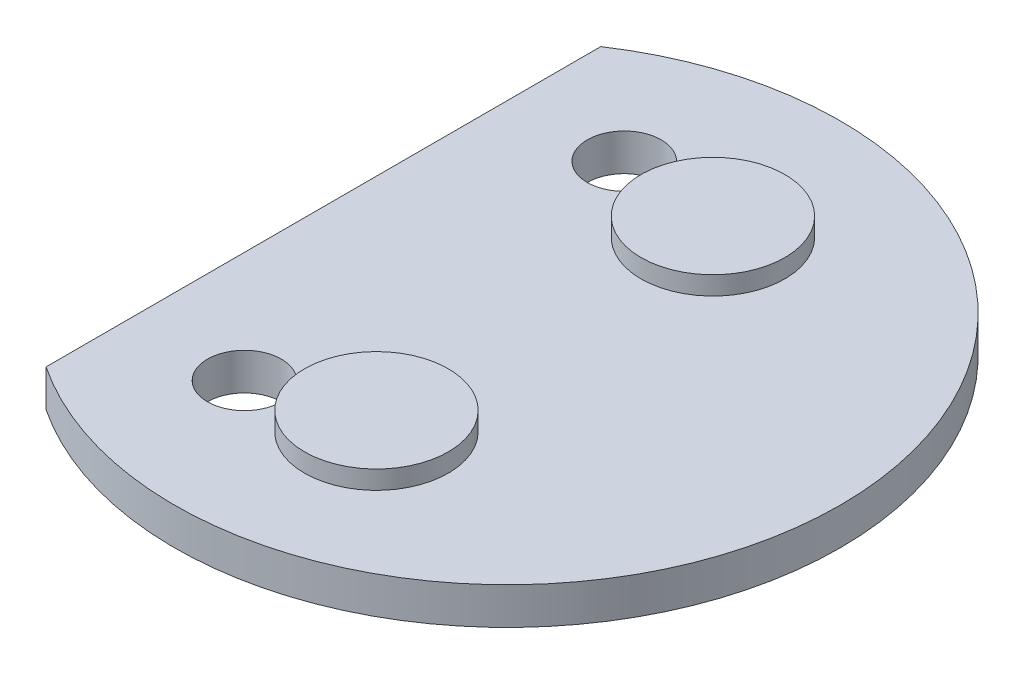
SolidWorks part; units mm, degrees
ref_plane "Plano frontal" through (0, 0, 0) normal (0, 0, 1) x (1, 0, 0)
ref_plane "Plano superior" through (0, 0, 0) normal (0, 1, 0) x (1, 0, 0)
ref_plane "Plano direito" through (0, 0, 0) normal (1, 0, 0) x (0, 0, -1)
sketch "Esboço4" plane through (0, 0, 0) normal (0, 1, 0) x (1, 0, 0)
  line L0 (4.9701, 2.0623) -> (4.9701, -12.9377)
  circle A1 centre (9.9451, -5.4377) radius 9
  dimension "D4" = 18
  dimension "D3" = 15
other "Alinhar grupo1"
extrude "Ressalto-extrusão2" add sketch "Esboço4" along normal blind 1.5 contours L0 A1
sketch "Esboço5" plane through (0, 1.5, 0) normal (0, 1, 0) x (1, 0, 0)
  circle A1 centre (10.9534, -0.8885) radius 1.945
  circle A2 centre (10.9534, -9.9869) radius 1.945
  circle A3 centre (8.28, -5.1612) radius 15.7275
extrude "Corte-extrusão1" cut sketch "Esboço5" against normal blind 0.5
sketch "Esboço7" plane through (0, 1, 0) normal (0, 1, 0) x (1, 0, 0)
  line L1 (4.9701, -5.4377) -> (18.9451, -5.4377) construction
  line L3 (4.9701, 2.0623) -> (4.9701, -12.9377) construction
  circle A0 centre (7.9701, -10.5724) radius 1
  circle A2 centre (7.9701, -0.303) radius 1
  point P13 (6.9701, -10.5724)
  dimension "D1" = 3
extrude "Corte-extrusão2" cut sketch "Esboço7" against normal through all and the other way through all
